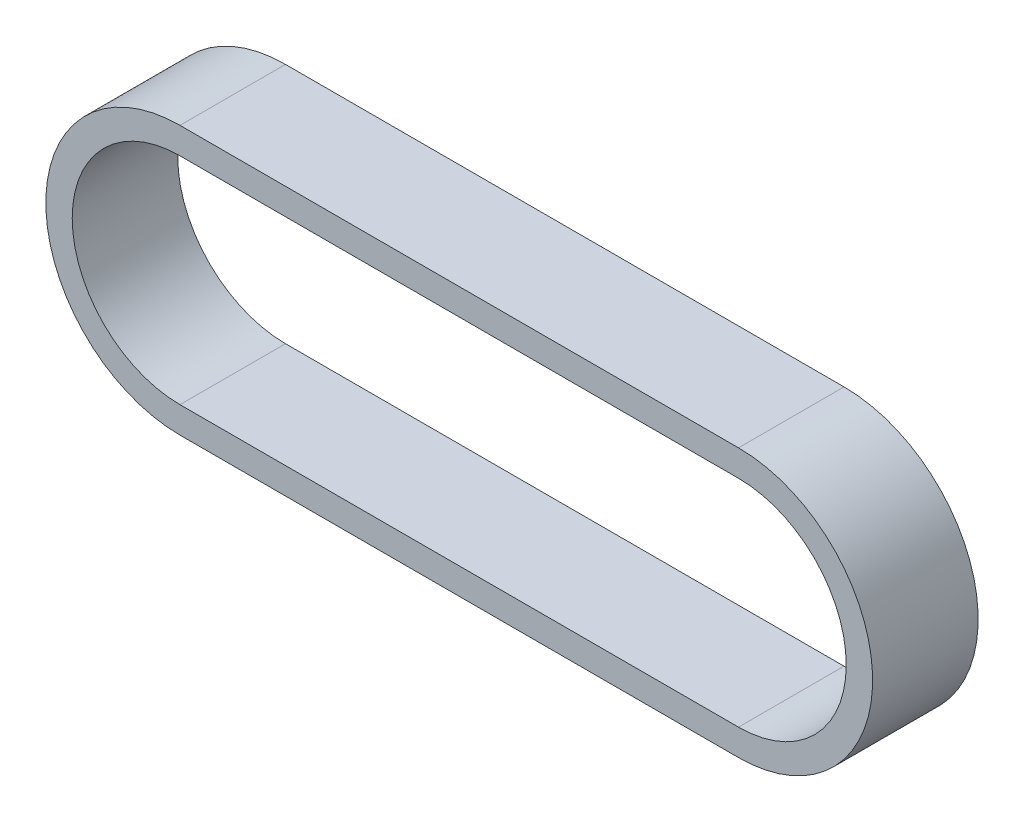
SolidWorks part; units mm, degrees
ref_plane "Front Plane" through (0, 0, 0) normal (0, 0, 1) x (1, 0, 0)
ref_plane "Top Plane" through (0, 0, 0) normal (0, 1, 0) x (1, 0, 0)
ref_plane "Right Plane" through (0, 0, 0) normal (1, 0, 0) x (0, 0, -1)
sketch "Sketch4" plane through (0, 0, 0) normal (0, 0, 1) x (1, 0, 0)
  line L0 (0, 0) -> (31.75, 0) construction
  line L1 (0, 6.125) -> (31.75, 6.125)
  line L2 (0, -6.125) -> (31.75, -6.125)
  line L3 (0, 0) -> (31.75, 0) construction
  line L4 (0, 7.625) -> (31.75, 7.625)
  line L5 (0, -7.625) -> (31.75, -7.625)
  arc A0 (0, 6.125) -> (0, -6.125) centre (0, 0) ccw
  arc A1 (31.75, -6.125) -> (31.75, 6.125) centre (31.75, 0) ccw
  arc A2 (0, 7.625) -> (0, -7.625) centre (0, 0) ccw
  arc A3 (31.75, -7.625) -> (31.75, 7.625) centre (31.75, 0) ccw
  point P3 (15.875, 0)
  point P10 (15.875, 0)
  dimension "D1" = 31.75
  dimension "D2" = 6.125
  dimension "D3" = 1.5
extrude "Boss-Extrude1" add sketch "Sketch4" along normal blind 6
